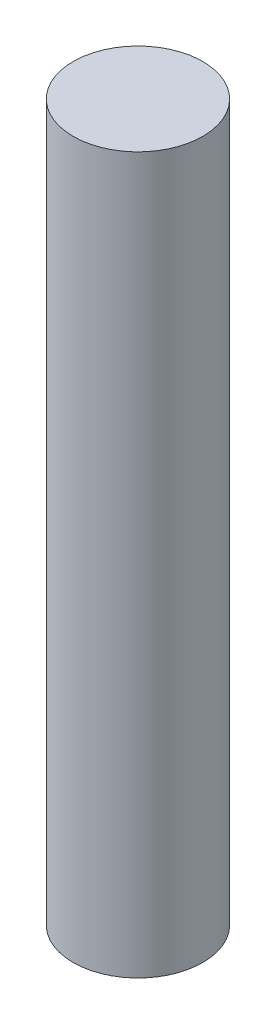
SolidWorks part; units mm, degrees
ref_plane "Front Plane" through (0, 0, 0) normal (0, 0, 1) x (1, 0, 0)
ref_plane "Top Plane" through (0, 0, 0) normal (0, 1, 0) x (1, 0, 0)
ref_plane "Right Plane" through (0, 0, 0) normal (1, 0, 0) x (0, 0, -1)
sketch "Sketch1" plane through (0, 0, 0) normal (0, 1, 0) x (1, 0, 0)
  circle A0 centre (1299.2899, 0) radius 371.5772
extrude "Boss-Extrude1" add sketch "Sketch1" along normal blind 4100 from offset 2050
